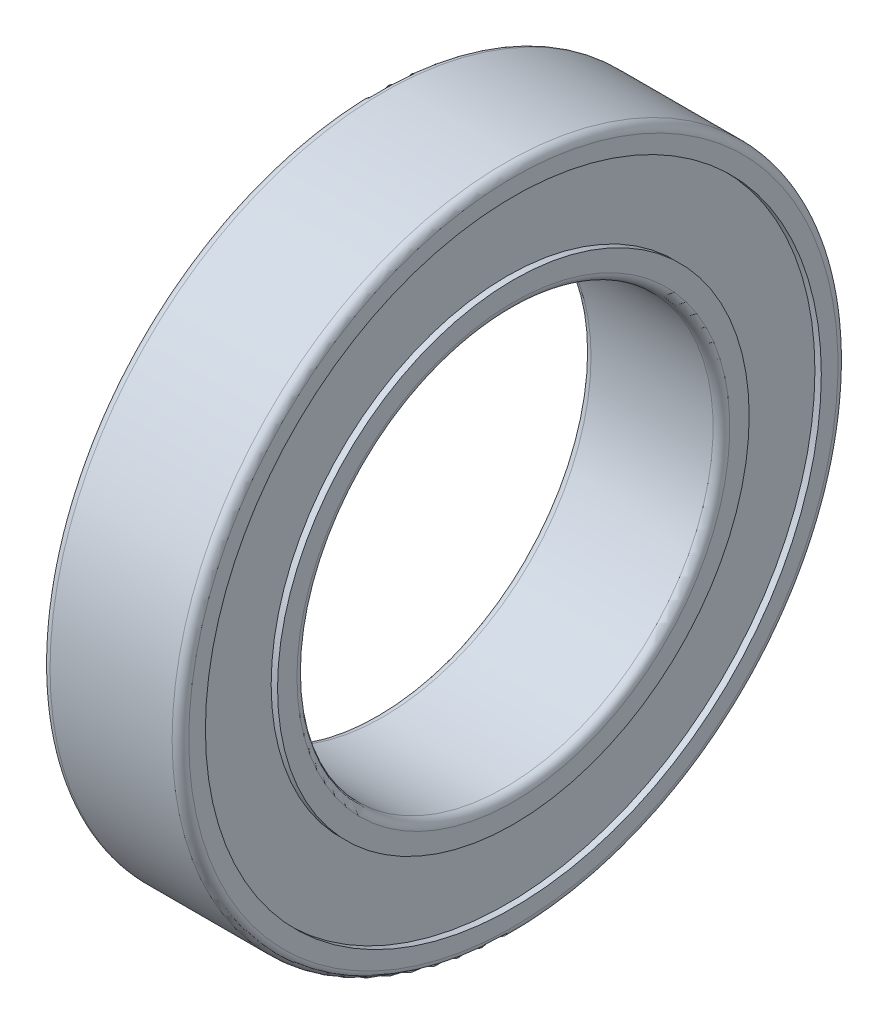
SolidWorks part; units mm, degrees
material "炭素鋼(普通)"
ref_plane "Front Plane" through (0, 0, 0) normal (0, 0, 1) x (1, 0, 0)
ref_plane "Top Plane" through (0, 0, 0) normal (0, 1, 0) x (1, 0, 0)
ref_plane "Right Plane" through (0, 0, 0) normal (1, 0, 0) x (0, 0, -1)
sketch "Sketch1" plane through (0, 0, 0) normal (0, 0, 1) x (1, 0, 0)
  line L0 (0, 0) -> (5, 0) construction
  line L1 (0, 7.5) -> (5, 7.5)
  line L2 (0, 12) -> (5, 12)
  line L3 (0, 12) -> (0, 11.1)
  line L4 (0, 11.1) -> (0.23, 11.1)
  line L5 (5, 12) -> (5, 11.1)
  line L6 (0.23, 11.1) -> (0.23, 8.5)
  line L7 (0.23, 8.5) -> (0, 8.5)
  line L8 (0, 8.5) -> (0, 7.5)
  line L9 (5, 11.1) -> (4.77, 11.1)
  line L10 (4.77, 11.1) -> (4.77, 8.5)
  line L11 (4.77, 8.5) -> (5, 8.5)
  line L12 (5, 8.5) -> (5, 7.5)
  dimension "D" = 24
  dimension "B" = 5
  dimension "D_s" = 15
  dimension "MSM_1" = 22.2
  dimension "MSM_2" = 17
  dimension "MSM_3" = 0.23
revolve "Revolve1" add sketch "Sketch1" angle 360 about L0
fillet "Fillet1" radius 0.3 2 edges at (5, 0, 12) (0, 0, 12)
fillet "Fillet2" radius 0.3 2 edges at (5, 0, 7.5) (0, 0, 7.5)
